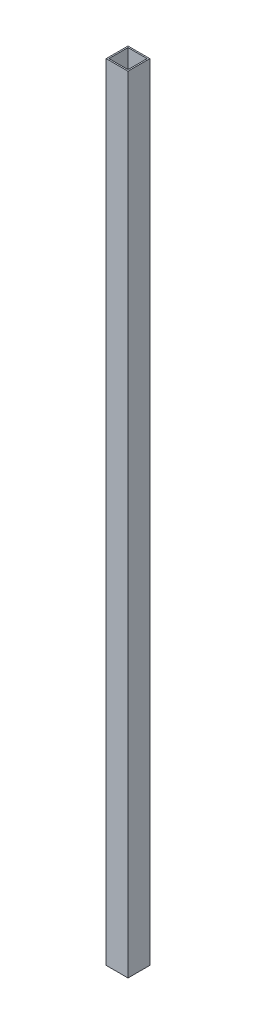
SolidWorks part; units mm, degrees
ref_plane "Front Plane" through (0, 0, 0) normal (0, 0, 1) x (1, 0, 0)
ref_plane "Top Plane" through (0, 0, 0) normal (0, 1, 0) x (1, 0, 0)
ref_plane "Right Plane" through (0, 0, 0) normal (1, 0, 0) x (0, 0, -1)
sketch "Sketch1" plane through (0, 0, 0) normal (0, 1, 0) x (1, 0, 0)
  line L1 (0, 0) -> (25.4, 0)
  line L2 (0, 0) -> (0, 25.4)
  line L3 (0, 25.4) -> (25.4, 25.4)
  line L4 (25.4, 0) -> (25.4, 25.4)
  line L5 (1.5875, 23.8125) -> (23.8125, 23.8125)
  line L6 (1.5875, 23.8125) -> (1.5875, 1.5875)
  line L7 (1.5875, 1.5875) -> (23.8125, 1.5875)
  line L8 (23.8125, 23.8125) -> (23.8125, 1.5875)
  point P9 (1.5875, 12.7)
  point P10 (12.7, 23.8125)
  point P11 (23.8125, 12.7)
  dimension "D1" = 25.4
  dimension "D2" = 25.4
  dimension "D3" = 1.5875
  dimension "D4" = 1.5875
  dimension "D5" = 1.5875
  dimension "D6" = 1.5875
extrude "Boss-Extrude1" add sketch "Sketch1" along normal blind 914.4
